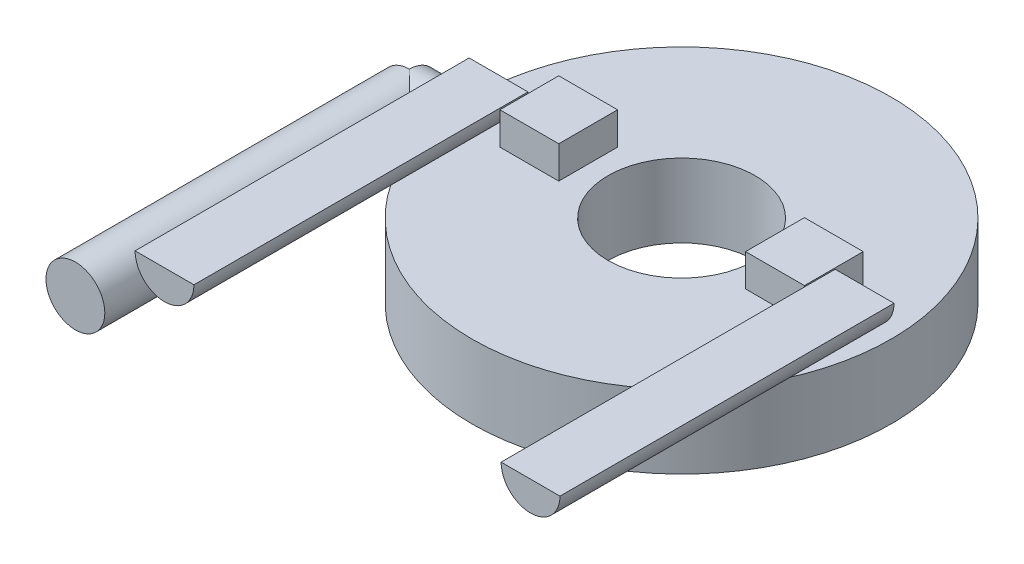
SolidWorks part; units mm, degrees
ref_plane "Front Plane" through (0, 0, 0) normal (0, 0, 1) x (1, 0, 0)
ref_plane "Top Plane" through (0, 0, 0) normal (0, 1, 0) x (1, 0, 0)
ref_plane "Right Plane" through (0, 0, 0) normal (1, 0, 0) x (0, 0, -1)
sketch "Sketch2" plane through (0, 0, 0) normal (0, 1, 0) x (1, 0, 0)
  circle A0 centre (0, 0) radius 5
  circle A1 centre (0, 0) radius 14.25
  dimension "D1" = 10
  dimension "D2" = 28.5
extrude "Boss-Extrude1" add sketch "Sketch2" along normal blind 5
sketch "Sketch3" plane through (0, 5, 0) normal (0, 1, 0) x (1, 0, 0)
  line L0 (0, 0) -> (24.0284, 0) construction
  line L1 (24.0284, 0) -> (-21.3668, 0) construction
  line L2 (-21.3668, 0) -> (0, 0) construction
  line L3 (0, 0) -> (0, -31.6834) construction
  line L4 (0, 25.8144) -> (0, 0) construction
  line L5 (-6.35, -17.767) -> (-6.35, 16.5683) construction
  line L6 (-6.35, 16.5683) -> (6.35, 16.5683) construction
  line L7 (6.35, 16.5683) -> (6.35, -21.1723) construction
  line L8 (6.35, 2) -> (6.35, -2)
  line L9 (-10.35, 2) -> (-6.35, 2)
  line L10 (-10.35, 2) -> (-10.35, -2)
  line L11 (-10.35, -2) -> (-6.35, -2)
  line L12 (-6.35, 2) -> (-6.35, -2)
  line L13 (10.35, -2) -> (6.35, -2)
  line L14 (10.35, 2) -> (10.35, -2)
  line L15 (10.35, 2) -> (6.35, 2)
  dimension "D1" = 6.35
  dimension "D2" = 6.35
  dimension "D3" = 4
  dimension "D4" = 4
extrude "Boss-Extrude2" add sketch "Sketch3" along normal blind 2.2
sketch "Sketch4" plane through (10.35, 0, 0) normal (1, 0, 0) x (0, 0, -1)
  line L0 (0, 12.2999) -> (0, -3.5336) construction
  circle A0 centre (0, 5.4753) radius 0.5
  dimension "D1" = 1
extrude "Boss-Extrude3" add sketch "Sketch4" along normal blind 2
sketch "Sketch6" plane through (-10.35, 0, 0) normal (-1, 0, 0) x (0, 0, 1)
  line L0 (0, 10.7221) -> (0, 2.6163) construction
  circle A0 centre (0, 5.4359) radius 0.5
  dimension "D1" = 1
extrude "Boss-Extrude4" add sketch "Sketch6" along normal blind 2
sketch "Sketch13" plane through (0, 0, 0) normal (0, 0, 1) x (1, 0, 0)
  line L0 (0, 20.2821) -> (0, -3.7206) construction
  circle A0 centre (-12.4416, 7.2056) radius 2
  circle A1 centre (12.4416, 7.2056) radius 2
extrude "Boss-Extrude12" add sketch "Sketch13" along normal blind 50
ref_plane "Plane2" through (-14.5, 0, 0) normal (1, 0, 0) x (0, 0, -1)
sketch "Sketch15" plane through (-14.5, 0, 0) normal (1, 0, 0) x (0, 0, -1)
  circle A0 centre (0, 2.517) radius 2
  dimension "D1" = 4
extrude "Boss-Extrude13" add sketch "Sketch15" against normal blind 4 separate body
sketch "Sketch16" plane through (0, 11.711, 0) normal (0, 0, 1) x (1, 0, 0)
  line L0 (-18.5, -7.194) -> (-18.5, -11.194) construction
  circle A0 centre (-18.5, -9.194) radius 2
  dimension "D1" = 4
extrude "Boss-Extrude14" add sketch "Sketch16" along normal blind 60
sketch "Sketch17" plane through (0, 0, 0) normal (0, 0, -1) x (-1, 0, 0)
  line L1 (14.4416, 7.2056) -> (-16.37, 7.2056)
  line L2 (14.4416, 7.2056) -> (14.4416, 11.6876)
  line L3 (14.4416, 11.6876) -> (-16.37, 11.6876)
  line L4 (-16.37, 7.2056) -> (-16.37, 11.6876)
  arc A0 (12.35, 5.2077) -> (10.8964, 5.9359) centre (12.4416, 7.2056) ccw construction
extrude "Cut-Extrude1" cut sketch "Sketch17" against normal blind 10.8
ref_plane "Plane3" through (0, 0, 22.71) normal (0, 0, 1) x (1, 0, 0)
sketch "Sketch18" plane through (0, 0, 22.71) normal (0, 0, 1) x (1, 0, 0)
  line L1 (-49.9798, 35.0535) -> (43.1638, 35.0535)
  line L2 (-49.9798, 35.0535) -> (-49.9798, -32.5169)
  line L3 (-49.9798, -32.5169) -> (43.1638, -32.5169)
  line L4 (43.1638, 35.0535) -> (43.1638, -32.5169)
extrude "Cut-Extrude2" cut sketch "Sketch18" along normal blind 43
sketch "Sketch19" plane through (0, 7.2056, 0) normal (0, 1, 0) x (1, 0, 0)
  line L1 (-37.82, 17.7114) -> (45.0889, 17.7114)
  line L2 (-37.82, 17.7114) -> (-37.82, -40.5039)
  line L3 (-37.82, -40.5039) -> (45.0889, -40.5039)
  line L4 (45.0889, 17.7114) -> (45.0889, -40.5039)
extrude "Cut-Extrude3" cut sketch "Sketch19" along normal blind 8
